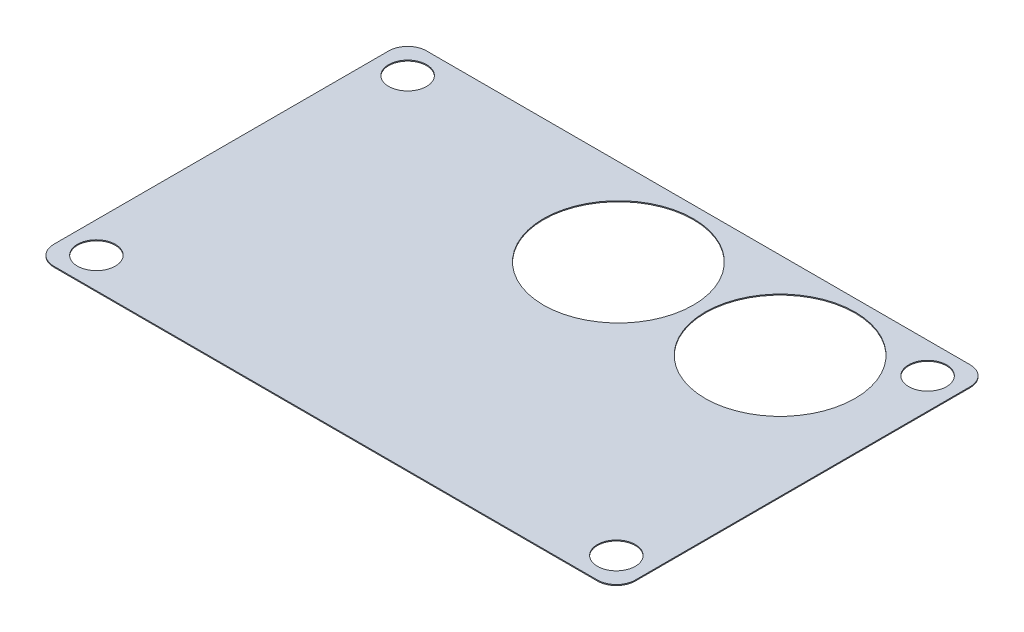
SolidWorks part; units mm, degrees
ref_plane "Front Plane" through (0, 0, 0) normal (0, 0, 1) x (1, 0, 0)
ref_plane "Top Plane" through (0, 0, 0) normal (0, 1, 0) x (1, 0, 0)
ref_plane "Right Plane" through (0, 0, 0) normal (1, 0, 0) x (0, 0, -1)
sketch "Sketch1" plane through (0, 0, 0) normal (0, 1, 0) x (1, 0, 0)
  line L1 (0, 0) -> (78, 0)
  line L2 (0, 0) -> (0, 50)
  line L3 (0, 50) -> (78, 50)
  line L4 (78, 0) -> (78, 50)
  dimension "D1" = 78
  dimension "D2" = 50
extrude "kapton_insulation" add sketch "Sketch1" along normal blind 0.127
fillet "edge_radius" radius 2.54 4 edges at (78, 0.0635, 0) (78, 0.0635, -50) (0, 0.0635, -50) (0, 0.0635, 0)
sketch "Sketch3" plane through (0, 0.127, 0) normal (0, 1, 0) x (1, 0, 0)
  line L1 (2.54, 0) -> (75.46, 0) construction
  line L2 (0, 47.46) -> (0, 2.54) construction
  circle A0 centre (4.1275, 4.1275) radius 2.54
  dimension "D1" = 5.08
  dimension "D2" = 1.5875
  dimension "D3" = 1.5875
extrude "magnet_hole" cut sketch "Sketch3" against normal through all
ref_plane "Plane1" through (0, 0, -25) normal (0, 0, 1) x (1, 0, 0)
ref_plane "Plane2" through (39, 0, 0) normal (1, 0, 0) x (0, 0, -1)
mirror "Mirror1" about plane through (0, 0, -25) normal (0, 0, 1) of "magnet_hole"
mirror "Mirror2" about plane through (39, 0, 0) normal (1, 0, 0) of "Mirror1", "magnet_hole"
sketch "Sketch4" plane through (0, 0.127, 0) normal (0, 1, 0) x (1, 0, 0)
  line L1 (75.46, 50) -> (2.54, 50) construction
  line L2 (78, 2.54) -> (78, 47.46) construction
  circle A0 centre (61.6, 38.3625) radius 10.05
  circle A1 centre (39.9125, 38.3625) radius 10.05
  dimension "D2" = 1.5875
  dimension "D1" = 20.1
  dimension "D3" = 6.35
  dimension "D4" = 1.5875
extrude "Cut-Extrude2" cut sketch "Sketch4" against normal through all
equation "\"magnet_inset\"= 0.0625in"
equation "\"magnet_diameter\" = 0.2in"
equation "\"steel_inset_distance\" = 1in / 32"
equation "\"kapton_thickness\"= 0.005in"
equation "\"pcb_thickness\"= 0.6mm"
equation "\"magnet_thickness\" = 0.03125in"
equation "\"edge_radius\" = 1in / 10"
equation "\"D1@edge_radius\" = \"edge_radius\""
equation "\"D1@Sketch3\"=\"magnet_diameter\""
equation "\"D2@Sketch3\"=\"magnet_inset\""
equation "\"D3@Sketch3\"=\"magnet_inset\""
equation "\"card_height\" = 50mm"
equation "\"D2@Sketch1\"=\"card_height\""
equation "\"card_width\" = 78mm"
equation "\"D1@Sketch1\"=\"card_width\""
equation "\"D1@Plane1\"=\"card_height\"/2"
equation "\"D1@Plane2\"=\"card_width\"/2"
equation "\"battery_diameter\" = 20mm"
equation "\"battery_oversize\" = 0.1mm"
equation "\"D1@Sketch4\"=\"battery_diameter\"+\"battery_oversize\""
equation "\"battery_vertical_inset\" = 1in / 16"
equation "\"D2@Sketch4\"=\"battery_vertical_inset\""
equation "\"battery_horizontal_inset\" = 1in / 4"
equation "\"D3@Sketch4\"=\"battery_horizontal_inset\""
equation "\"battery_spacing\" = 1in / 16"
equation "\"D4@Sketch4\"=\"battery_spacing\""
